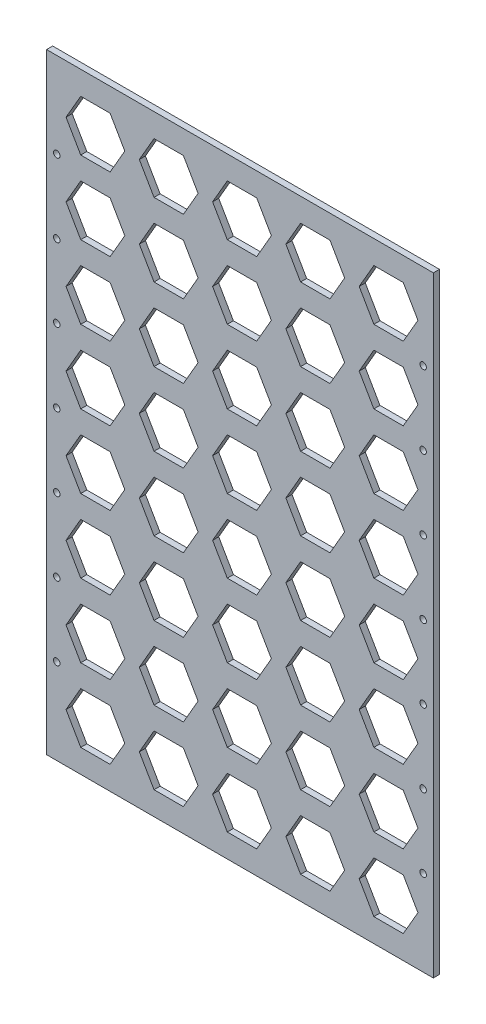
SolidWorks part; units mm, degrees
material "有机玻璃 (TM) GS 丙烯酸铸钣"
ref_plane "前视基准面" through (0, 0, 0) normal (0, 0, 1) x (1, 0, 0)
ref_plane "上视基准面" through (0, 0, 0) normal (0, 1, 0) x (1, 0, 0)
ref_plane "右视基准面" through (0, 0, 0) normal (1, 0, 0) x (0, 0, -1)
other "Configuration Table"
sketch "草图1" plane through (0, 0, 0) normal (0, 0, 1) x (1, 0, 0)
  line L1 (0, 0) -> (190, 0)
  line L2 (0, 0) -> (0, -300)
  line L3 (0, -300) -> (190, -300)
  line L4 (190, 0) -> (190, -300)
  dimension "D1" = 190
  dimension "D2" = 300
extrude "凸台-拉伸1" add sketch "草图1" along normal blind 3
sketch "草图2" plane through (0, 0, 3) normal (0, 0, 1) x (1, 0, 0)
  line L0 (0, 0) -> (0, -300) construction
  line L1 (38.4338, -24) -> (31.2169, -11.5)
  line L2 (31.2169, -11.5) -> (16.7831, -11.5)
  line L3 (16.7831, -11.5) -> (9.5662, -24)
  line L4 (9.5662, -24) -> (16.7831, -36.5)
  line L5 (16.7831, -36.5) -> (31.2169, -36.5)
  line L6 (31.2169, -36.5) -> (38.4338, -24)
  line L7 (190, 0) -> (0, 0) construction
  line L8 (67.2169, -11.5) -> (52.7831, -11.5)
  line L9 (52.7831, -11.5) -> (45.5662, -24)
  line L10 (45.5662, -24) -> (52.7831, -36.5)
  line L11 (52.7831, -36.5) -> (67.2169, -36.5)
  line L12 (67.2169, -36.5) -> (74.4338, -24)
  line L13 (74.4338, -24) -> (67.2169, -11.5)
  line L14 (103.2169, -11.5) -> (88.7831, -11.5)
  line L15 (88.7831, -11.5) -> (81.5662, -24)
  line L16 (81.5662, -24) -> (88.7831, -36.5)
  line L17 (88.7831, -36.5) -> (103.2169, -36.5)
  line L18 (103.2169, -36.5) -> (110.4338, -24)
  line L19 (110.4338, -24) -> (103.2169, -11.5)
  line L20 (139.2169, -11.5) -> (124.7831, -11.5)
  line L21 (124.7831, -11.5) -> (117.5662, -24)
  line L22 (117.5662, -24) -> (124.7831, -36.5)
  line L23 (124.7831, -36.5) -> (139.2169, -36.5)
  line L24 (139.2169, -36.5) -> (146.4338, -24)
  line L25 (146.4338, -24) -> (139.2169, -11.5)
  line L26 (175.2169, -11.5) -> (160.7831, -11.5)
  line L27 (160.7831, -11.5) -> (153.5662, -24)
  line L28 (153.5662, -24) -> (160.7831, -36.5)
  line L29 (160.7831, -36.5) -> (175.2169, -36.5)
  line L30 (175.2169, -36.5) -> (182.4338, -24)
  line L31 (182.4338, -24) -> (175.2169, -11.5)
  line L32 (67.2169, -47.5) -> (52.7831, -47.5)
  line L33 (52.7831, -47.5) -> (45.5662, -60)
  line L34 (45.5662, -60) -> (52.7831, -72.5)
  line L35 (52.7831, -72.5) -> (67.2169, -72.5)
  line L36 (67.2169, -72.5) -> (74.4338, -60)
  line L37 (74.4338, -60) -> (67.2169, -47.5)
  line L38 (103.2169, -47.5) -> (88.7831, -47.5)
  line L39 (88.7831, -47.5) -> (81.5662, -60)
  line L40 (81.5662, -60) -> (88.7831, -72.5)
  line L41 (88.7831, -72.5) -> (103.2169, -72.5)
  line L42 (103.2169, -72.5) -> (110.4338, -60)
  line L43 (110.4338, -60) -> (103.2169, -47.5)
  line L44 (139.2169, -47.5) -> (124.7831, -47.5)
  line L45 (124.7831, -47.5) -> (117.5662, -60)
  line L46 (117.5662, -60) -> (124.7831, -72.5)
  line L47 (124.7831, -72.5) -> (139.2169, -72.5)
  line L48 (139.2169, -72.5) -> (146.4338, -60)
  line L49 (146.4338, -60) -> (139.2169, -47.5)
  line L50 (175.2169, -47.5) -> (160.7831, -47.5)
  line L51 (160.7831, -47.5) -> (153.5662, -60)
  line L52 (153.5662, -60) -> (160.7831, -72.5)
  line L53 (160.7831, -72.5) -> (175.2169, -72.5)
  line L54 (175.2169, -72.5) -> (182.4338, -60)
  line L55 (182.4338, -60) -> (175.2169, -47.5)
  line L56 (67.2169, -83.5) -> (52.7831, -83.5)
  line L57 (52.7831, -83.5) -> (45.5662, -96)
  line L58 (45.5662, -96) -> (52.7831, -108.5)
  line L59 (52.7831, -108.5) -> (67.2169, -108.5)
  line L60 (67.2169, -108.5) -> (74.4338, -96)
  line L61 (74.4338, -96) -> (67.2169, -83.5)
  line L62 (103.2169, -83.5) -> (88.7831, -83.5)
  line L63 (88.7831, -83.5) -> (81.5662, -96)
  line L64 (81.5662, -96) -> (88.7831, -108.5)
  line L65 (88.7831, -108.5) -> (103.2169, -108.5)
  line L66 (103.2169, -108.5) -> (110.4338, -96)
  line L67 (110.4338, -96) -> (103.2169, -83.5)
  line L68 (139.2169, -83.5) -> (124.7831, -83.5)
  line L69 (124.7831, -83.5) -> (117.5662, -96)
  line L70 (117.5662, -96) -> (124.7831, -108.5)
  line L71 (124.7831, -108.5) -> (139.2169, -108.5)
  line L72 (139.2169, -108.5) -> (146.4338, -96)
  line L73 (146.4338, -96) -> (139.2169, -83.5)
  line L74 (175.2169, -83.5) -> (160.7831, -83.5)
  line L75 (160.7831, -83.5) -> (153.5662, -96)
  line L76 (153.5662, -96) -> (160.7831, -108.5)
  line L77 (160.7831, -108.5) -> (175.2169, -108.5)
  line L78 (175.2169, -108.5) -> (182.4338, -96)
  line L79 (182.4338, -96) -> (175.2169, -83.5)
  line L80 (67.2169, -119.5) -> (52.7831, -119.5)
  line L81 (52.7831, -119.5) -> (45.5662, -132)
  line L82 (45.5662, -132) -> (52.7831, -144.5)
  line L83 (52.7831, -144.5) -> (67.2169, -144.5)
  line L84 (67.2169, -144.5) -> (74.4338, -132)
  line L85 (74.4338, -132) -> (67.2169, -119.5)
  line L86 (103.2169, -119.5) -> (88.7831, -119.5)
  line L87 (88.7831, -119.5) -> (81.5662, -132)
  line L88 (81.5662, -132) -> (88.7831, -144.5)
  line L89 (88.7831, -144.5) -> (103.2169, -144.5)
  line L90 (103.2169, -144.5) -> (110.4338, -132)
  line L91 (110.4338, -132) -> (103.2169, -119.5)
  line L92 (139.2169, -119.5) -> (124.7831, -119.5)
  line L93 (124.7831, -119.5) -> (117.5662, -132)
  line L94 (117.5662, -132) -> (124.7831, -144.5)
  line L95 (124.7831, -144.5) -> (139.2169, -144.5)
  line L96 (139.2169, -144.5) -> (146.4338, -132)
  line L97 (146.4338, -132) -> (139.2169, -119.5)
  line L98 (175.2169, -119.5) -> (160.7831, -119.5)
  line L99 (160.7831, -119.5) -> (153.5662, -132)
  line L100 (153.5662, -132) -> (160.7831, -144.5)
  line L101 (160.7831, -144.5) -> (175.2169, -144.5)
  line L102 (175.2169, -144.5) -> (182.4338, -132)
  line L103 (182.4338, -132) -> (175.2169, -119.5)
  line L104 (67.2169, -155.5) -> (52.7831, -155.5)
  line L105 (52.7831, -155.5) -> (45.5662, -168)
  line L106 (45.5662, -168) -> (52.7831, -180.5)
  line L107 (52.7831, -180.5) -> (67.2169, -180.5)
  line L108 (67.2169, -180.5) -> (74.4338, -168)
  line L109 (74.4338, -168) -> (67.2169, -155.5)
  line L110 (103.2169, -155.5) -> (88.7831, -155.5)
  line L111 (88.7831, -155.5) -> (81.5662, -168)
  line L112 (81.5662, -168) -> (88.7831, -180.5)
  line L113 (88.7831, -180.5) -> (103.2169, -180.5)
  line L114 (103.2169, -180.5) -> (110.4338, -168)
  line L115 (110.4338, -168) -> (103.2169, -155.5)
  line L116 (139.2169, -155.5) -> (124.7831, -155.5)
  line L117 (124.7831, -155.5) -> (117.5662, -168)
  line L118 (117.5662, -168) -> (124.7831, -180.5)
  line L119 (124.7831, -180.5) -> (139.2169, -180.5)
  line L120 (139.2169, -180.5) -> (146.4338, -168)
  line L121 (146.4338, -168) -> (139.2169, -155.5)
  line L122 (175.2169, -155.5) -> (160.7831, -155.5)
  line L123 (160.7831, -155.5) -> (153.5662, -168)
  line L124 (153.5662, -168) -> (160.7831, -180.5)
  line L125 (160.7831, -180.5) -> (175.2169, -180.5)
  line L126 (175.2169, -180.5) -> (182.4338, -168)
  line L127 (182.4338, -168) -> (175.2169, -155.5)
  line L128 (67.2169, -191.5) -> (52.7831, -191.5)
  line L129 (52.7831, -191.5) -> (45.5662, -204)
  line L130 (45.5662, -204) -> (52.7831, -216.5)
  line L131 (52.7831, -216.5) -> (67.2169, -216.5)
  line L132 (67.2169, -216.5) -> (74.4338, -204)
  line L133 (74.4338, -204) -> (67.2169, -191.5)
  line L134 (103.2169, -191.5) -> (88.7831, -191.5)
  line L135 (88.7831, -191.5) -> (81.5662, -204)
  line L136 (81.5662, -204) -> (88.7831, -216.5)
  line L137 (88.7831, -216.5) -> (103.2169, -216.5)
  line L138 (103.2169, -216.5) -> (110.4338, -204)
  line L139 (110.4338, -204) -> (103.2169, -191.5)
  line L140 (139.2169, -191.5) -> (124.7831, -191.5)
  line L141 (124.7831, -191.5) -> (117.5662, -204)
  line L142 (117.5662, -204) -> (124.7831, -216.5)
  line L143 (124.7831, -216.5) -> (139.2169, -216.5)
  line L144 (139.2169, -216.5) -> (146.4338, -204)
  line L145 (146.4338, -204) -> (139.2169, -191.5)
  line L146 (175.2169, -191.5) -> (160.7831, -191.5)
  line L147 (160.7831, -191.5) -> (153.5662, -204)
  line L148 (153.5662, -204) -> (160.7831, -216.5)
  line L149 (160.7831, -216.5) -> (175.2169, -216.5)
  line L150 (175.2169, -216.5) -> (182.4338, -204)
  line L151 (182.4338, -204) -> (175.2169, -191.5)
  line L152 (67.2169, -227.5) -> (52.7831, -227.5)
  line L153 (52.7831, -227.5) -> (45.5662, -240)
  line L154 (45.5662, -240) -> (52.7831, -252.5)
  line L155 (52.7831, -252.5) -> (67.2169, -252.5)
  line L156 (67.2169, -252.5) -> (74.4338, -240)
  line L157 (74.4338, -240) -> (67.2169, -227.5)
  line L158 (103.2169, -227.5) -> (88.7831, -227.5)
  line L159 (88.7831, -227.5) -> (81.5662, -240)
  line L160 (81.5662, -240) -> (88.7831, -252.5)
  line L161 (88.7831, -252.5) -> (103.2169, -252.5)
  line L162 (103.2169, -252.5) -> (110.4338, -240)
  line L163 (110.4338, -240) -> (103.2169, -227.5)
  line L164 (139.2169, -227.5) -> (124.7831, -227.5)
  line L165 (124.7831, -227.5) -> (117.5662, -240)
  line L166 (117.5662, -240) -> (124.7831, -252.5)
  line L167 (124.7831, -252.5) -> (139.2169, -252.5)
  line L168 (139.2169, -252.5) -> (146.4338, -240)
  line L169 (146.4338, -240) -> (139.2169, -227.5)
  line L170 (175.2169, -227.5) -> (160.7831, -227.5)
  line L171 (160.7831, -227.5) -> (153.5662, -240)
  line L172 (153.5662, -240) -> (160.7831, -252.5)
  line L173 (160.7831, -252.5) -> (175.2169, -252.5)
  line L174 (175.2169, -252.5) -> (182.4338, -240)
  line L175 (182.4338, -240) -> (175.2169, -227.5)
  line L176 (67.2169, -263.5) -> (52.7831, -263.5)
  line L177 (52.7831, -263.5) -> (45.5662, -276)
  line L178 (45.5662, -276) -> (52.7831, -288.5)
  line L179 (52.7831, -288.5) -> (67.2169, -288.5)
  line L180 (67.2169, -288.5) -> (74.4338, -276)
  line L181 (74.4338, -276) -> (67.2169, -263.5)
  line L182 (103.2169, -263.5) -> (88.7831, -263.5)
  line L183 (88.7831, -263.5) -> (81.5662, -276)
  line L184 (81.5662, -276) -> (88.7831, -288.5)
  line L185 (88.7831, -288.5) -> (103.2169, -288.5)
  line L186 (103.2169, -288.5) -> (110.4338, -276)
  line L187 (110.4338, -276) -> (103.2169, -263.5)
  line L188 (139.2169, -263.5) -> (124.7831, -263.5)
  line L189 (124.7831, -263.5) -> (117.5662, -276)
  line L190 (117.5662, -276) -> (124.7831, -288.5)
  line L191 (124.7831, -288.5) -> (139.2169, -288.5)
  line L192 (139.2169, -288.5) -> (146.4338, -276)
  line L193 (146.4338, -276) -> (139.2169, -263.5)
  line L194 (175.2169, -263.5) -> (160.7831, -263.5)
  line L195 (160.7831, -263.5) -> (153.5662, -276)
  line L196 (153.5662, -276) -> (160.7831, -288.5)
  line L197 (160.7831, -288.5) -> (175.2169, -288.5)
  line L198 (175.2169, -288.5) -> (182.4338, -276)
  line L199 (182.4338, -276) -> (175.2169, -263.5)
  line L200 (31.2169, -47.5) -> (16.7831, -47.5)
  line L201 (16.7831, -47.5) -> (9.5662, -60)
  line L202 (9.5662, -60) -> (16.7831, -72.5)
  line L203 (16.7831, -72.5) -> (31.2169, -72.5)
  line L204 (31.2169, -72.5) -> (38.4338, -60)
  line L205 (38.4338, -60) -> (31.2169, -47.5)
  line L206 (31.2169, -83.5) -> (16.7831, -83.5)
  line L207 (16.7831, -83.5) -> (9.5662, -96)
  line L208 (9.5662, -96) -> (16.7831, -108.5)
  line L209 (16.7831, -108.5) -> (31.2169, -108.5)
  line L210 (31.2169, -108.5) -> (38.4338, -96)
  line L211 (38.4338, -96) -> (31.2169, -83.5)
  line L212 (31.2169, -119.5) -> (16.7831, -119.5)
  line L213 (16.7831, -119.5) -> (9.5662, -132)
  line L214 (9.5662, -132) -> (16.7831, -144.5)
  line L215 (16.7831, -144.5) -> (31.2169, -144.5)
  line L216 (31.2169, -144.5) -> (38.4338, -132)
  line L217 (38.4338, -132) -> (31.2169, -119.5)
  line L218 (31.2169, -155.5) -> (16.7831, -155.5)
  line L219 (16.7831, -155.5) -> (9.5662, -168)
  line L220 (9.5662, -168) -> (16.7831, -180.5)
  line L221 (16.7831, -180.5) -> (31.2169, -180.5)
  line L222 (31.2169, -180.5) -> (38.4338, -168)
  line L223 (38.4338, -168) -> (31.2169, -155.5)
  line L224 (31.2169, -191.5) -> (16.7831, -191.5)
  line L225 (16.7831, -191.5) -> (9.5662, -204)
  line L226 (9.5662, -204) -> (16.7831, -216.5)
  line L227 (16.7831, -216.5) -> (31.2169, -216.5)
  line L228 (31.2169, -216.5) -> (38.4338, -204)
  line L229 (38.4338, -204) -> (31.2169, -191.5)
  line L230 (31.2169, -227.5) -> (16.7831, -227.5)
  line L231 (16.7831, -227.5) -> (9.5662, -240)
  line L232 (9.5662, -240) -> (16.7831, -252.5)
  line L233 (16.7831, -252.5) -> (31.2169, -252.5)
  line L234 (31.2169, -252.5) -> (38.4338, -240)
  line L235 (38.4338, -240) -> (31.2169, -227.5)
  line L236 (31.2169, -263.5) -> (16.7831, -263.5)
  line L237 (16.7831, -263.5) -> (9.5662, -276)
  line L238 (9.5662, -276) -> (16.7831, -288.5)
  line L239 (16.7831, -288.5) -> (31.2169, -288.5)
  line L240 (31.2169, -288.5) -> (38.4338, -276)
  line L241 (38.4338, -276) -> (31.2169, -263.5)
  line L242 (16.7831, -11.5) -> (16.7831, -288.5) construction
  circle A0 centre (24, -24) radius 12.5 construction
  dimension "D1" = 25
  dimension "D2" = 24
  dimension "D3" = 24
  dimension "D4" = 5
  dimension "D6" = 36
  dimension "D7" = 36
  dimension "D5" = 8
extrude "切除-拉伸1" cut sketch "草图2" against normal blind 3
sketch "草图3" plane through (0, 0, 3) normal (0, 0, 1) x (1, 0, 0)
  line L0 (31.2169, -47.5) -> (16.7831, -47.5) construction
  line L1 (0, 0) -> (0, -300) construction
  circle A0 centre (5, -42) radius 1.6
  circle A1 centre (185, -42) radius 1.6
  circle A2 centre (5, -78) radius 1.6
  circle A3 centre (185, -78) radius 1.6
  circle A4 centre (5, -114) radius 1.6
  circle A5 centre (185, -114) radius 1.6
  circle A6 centre (5, -150) radius 1.6
  circle A7 centre (185, -150) radius 1.6
  circle A8 centre (5, -186) radius 1.6
  circle A9 centre (185, -186) radius 1.6
  circle A10 centre (5, -222) radius 1.6
  circle A11 centre (185, -222) radius 1.6
  circle A12 centre (5, -258) radius 1.6
  circle A13 centre (185, -258) radius 1.6
  dimension "D1" = 3.2
  dimension "D2" = 5.5
  dimension "D3" = 5
  dimension "D6" = 180
  dimension "D7" = 36
  dimension "D4" = 2
  dimension "D5" = 7
extrude "切除-拉伸2" cut sketch "草图3" against normal blind 10
